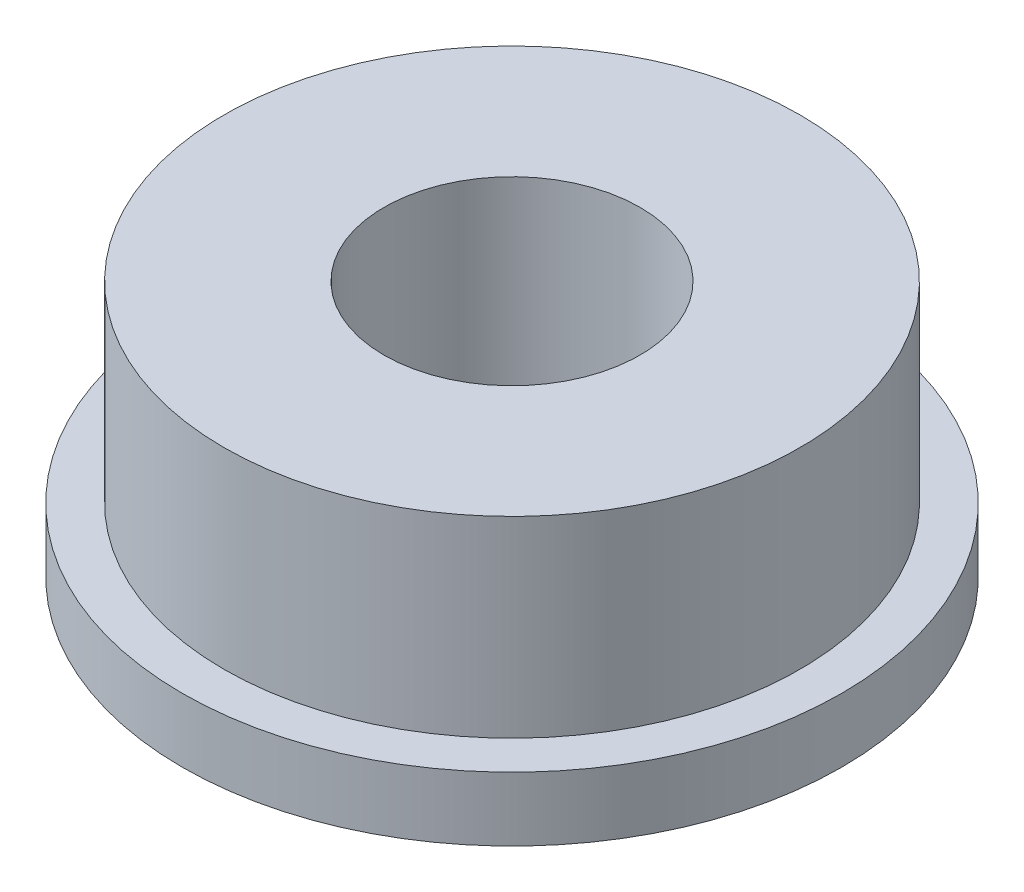
SolidWorks part; units mm, degrees
material "合金钢"
ref_plane "前视基准面" through (0, 0, 0) normal (0, 0, 1) x (1, 0, 0)
ref_plane "上视基准面" through (0, 0, 0) normal (0, 1, 0) x (1, 0, 0)
ref_plane "右视基准面" through (0, 0, 0) normal (1, 0, 0) x (0, 0, -1)
sketch "草图1" plane through (0, 0, 0) normal (0, 1, 0) x (1, 0, 0)
  circle A0 centre (0, 0) radius 5.15
  circle A1 centre (0, 0) radius 2
  dimension "D1" = 4
  dimension "D2" = 10.3
extrude "凸台-拉伸1" add sketch "草图1" along normal blind 1
sketch "草图2" plane through (0, 1, 0) normal (0, 1, 0) x (1, 0, 0)
  circle A0 centre (0, 0) radius 4.5
  circle A1 centre (0, 0) radius 2
  dimension "D1" = 9
extrude "凸台-拉伸2" add sketch "草图2" along normal blind 3
